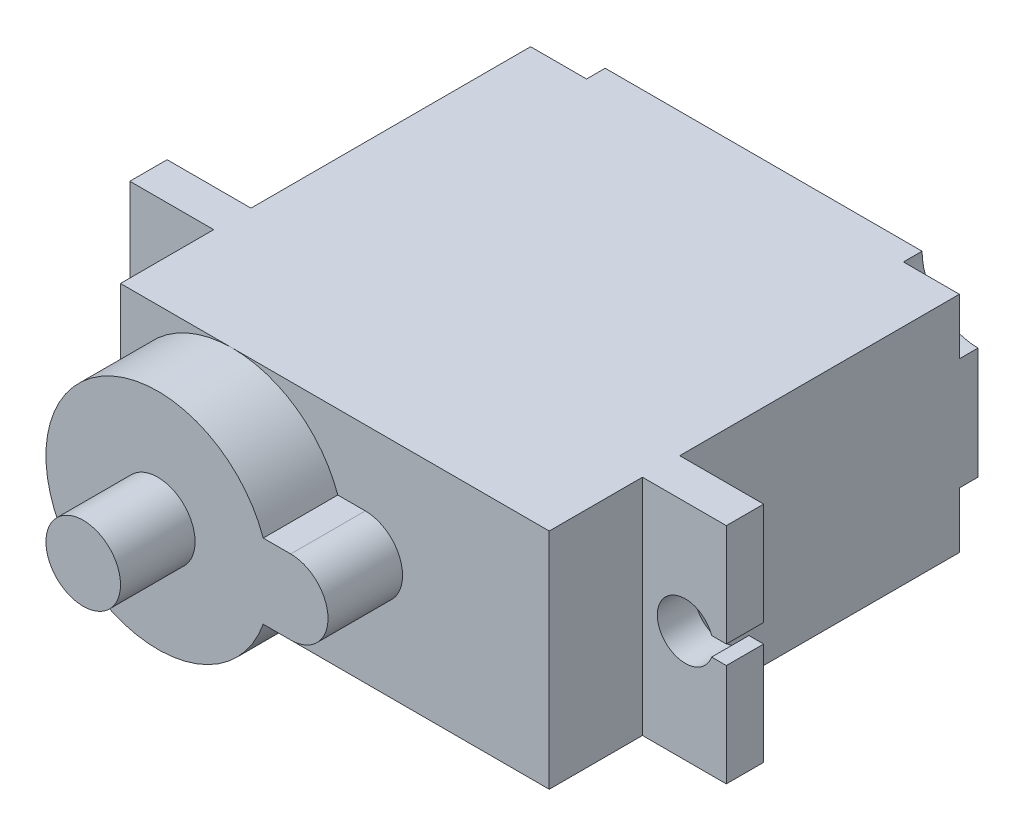
SolidWorks part; units mm, degrees
ref_plane "前视基准面" through (0, 0, 0) normal (0, 0, 1) x (1, 0, 0)
ref_plane "上视基准面" through (0, 0, 0) normal (0, 1, 0) x (1, 0, 0)
ref_plane "右视基准面" through (0, 0, 0) normal (1, 0, 0) x (0, 0, -1)
sketch "草图1" plane through (0, 0, 0) normal (0, 0, 1) x (1, 0, 0)
  line L1 (-11.5, 6) -> (11.5, 6)
  line L2 (-11.5, 6) -> (-11.5, -6)
  line L3 (-11.5, -6) -> (11.5, -6)
  line L4 (11.5, 6) -> (11.5, -6)
  line L5 (-11.5, 6) -> (11.5, -6) construction
  line L6 (-11.5, -6) -> (11.5, 6) construction
  point P0 (0, 0)
  dimension "D1" = 23
  dimension "D2" = 12
extrude "凸台-拉伸1" add sketch "草图1" along normal blind 16
sketch "草图2" plane through (0, 0, 16) normal (0, 0, 1) x (1, 0, 0)
  line L1 (-16, 6) -> (16, 6)
  line L2 (-16, 6) -> (-16, -6)
  line L3 (-16, -6) -> (16, -6)
  line L4 (16, 6) -> (16, -6)
  dimension "D1" = 32
  dimension "D2" = 16
extrude "凸台-拉伸2" add sketch "草图2" along normal blind 2
sketch "草图3" plane through (0, 0, 18) normal (0, 0, 1) x (1, 0, 0)
  line L4 (11.5, -6) -> (11.5, 6)
  line L5 (-11.5, -6) -> (11.5, -6)
  line L6 (-11.5, 6) -> (-11.5, -6)
  line L7 (11.5, 6) -> (-11.5, 6)
  line L8 (11.5, -6) -> (11.5, 6)
  line L9 (-11.5, -6) -> (11.5, -6)
  line L10 (-11.5, 6) -> (-11.5, -6)
  line L11 (11.5, 6) -> (-11.5, 6)
  dimension "D1" = 0
extrude "凸台-拉伸3" add sketch "草图3" along normal blind 5
sketch "草图4" plane through (0, 0, 23) normal (0, 0, 1) x (1, 0, 0)
  line L0 (-11.5, 6) -> (-11.5, -6) construction
  line L1 (1.6313, 2) -> (0.1569, 2)
  line L2 (1.6313, -2) -> (0.1569, -2)
  arc A0 (0.1569, 2) -> (0.1569, -2) centre (-5.5, 0) ccw
  arc A1 (1.6313, -2) -> (1.6313, 2) centre (1.6313, 0) ccw
  point P2 (-11.5, 0)
  dimension "D2" = 4
  dimension "D1" = 6
extrude "凸台-拉伸4" add sketch "草图4" along normal blind 4
sketch "草图6" plane through (0, 0, 27) normal (0, 0, 1) x (1, 0, 0)
  circle A0 centre (-5.5, 0) radius 2
  dimension "D1" = 4
extrude "凸台-拉伸5" add sketch "草图6" along normal blind 4
sketch "草图8" plane through (0, 0, 18) normal (0, 0, 1) x (1, 0, 0)
  line L0 (15.2119, 0.5) -> (16, 0.5)
  line L1 (16, -6) -> (16, 6) construction
  line L2 (16, 0.5) -> (16, -0.5)
  line L3 (16, -0.5) -> (15.2119, -0.5)
  arc A0 (15.2119, 0.5) -> (15.2119, -0.5) centre (13.7976, 0) ccw
  dimension "D1" = 3
  dimension "D2" = 1
  dimension "D3" = 0.5
extrude "切除-拉伸1" cut sketch "草图8" against normal blind 4
mirror "镜向1" about plane through (0, 0, 0) normal (1, 0, 0) of "切除-拉伸1"
sketch "草图9" plane through (0, 0, 0) normal (0, 0, -1) x (-1, 0, 0)
  circle A0 centre (11.5, 6) radius 3
  dimension "D1" = 6
extrude "切除-拉伸2" cut sketch "草图9" against normal blind 1
mirror "镜向2" about plane through (0, 0, 0) normal (1, 0, 0) of "切除-拉伸2"
mirror "镜向3" about plane through (0, 0, 0) normal (0, 1, 0) of "镜向2", "切除-拉伸2"
